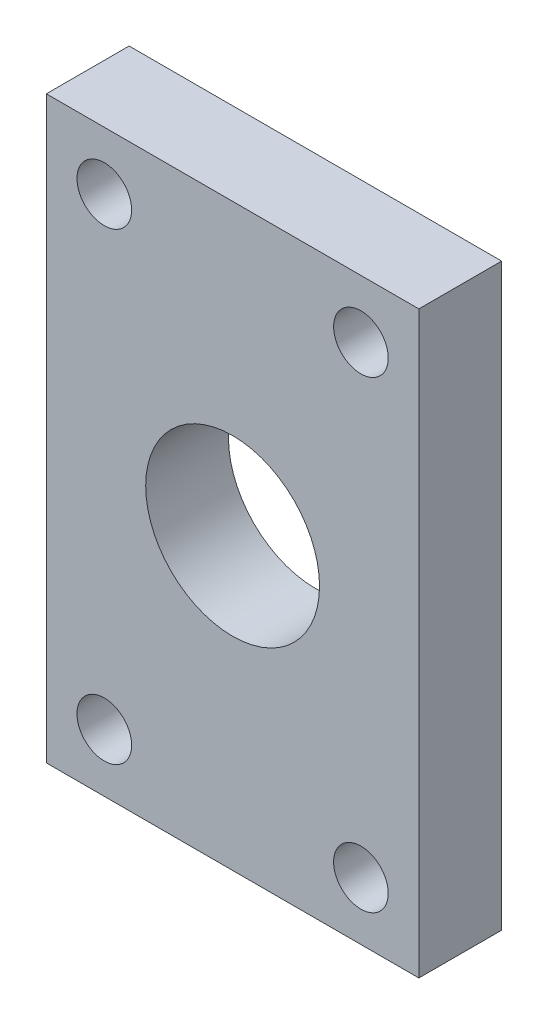
SolidWorks part; units mm, degrees
ref_plane "Piano frontale" through (0, 0, 0) normal (0, 0, 1) x (1, 0, 0)
ref_plane "Piano superiore" through (0, 0, 0) normal (0, 1, 0) x (1, 0, 0)
ref_plane "Piano destro" through (0, 0, 0) normal (1, 0, 0) x (0, 0, -1)
sketch "Schizzo1" plane through (0, 0, 0) normal (0, 0, 1) x (1, 0, 0)
  line L1 (0, 0) -> (45, 0)
  line L2 (0, 0) -> (0, 70)
  line L3 (0, 70) -> (45, 70)
  line L4 (45, 0) -> (45, 70)
  dimension "D1" = 70
  dimension "D2" = 45
extrude "Estrusione-Estrusione1" add sketch "Schizzo1" against normal blind 10
sketch "Schizzo2" plane through (0, 0, 0) normal (0, 0, 1) x (1, 0, 0)
  line L0 (22.5, 70) -> (22.5, 0) construction
  line L1 (45, 70) -> (0, 70) construction
  line L2 (0, 0) -> (45, 0) construction
  line L3 (45, 0) -> (23.1103, 0) construction
  line L4 (45, 0) -> (45, 70) construction
  line L5 (45, 35) -> (22.5, 35) construction
  line L6 (45, 7) -> (23.1103, 7) construction
  line L7 (45, 0) -> (45, 31.4323) construction
  line L8 (38, 0) -> (38, 31.4323) construction
  circle A0 centre (22.5, 35) radius 10.5
  circle A1 centre (38, 7) radius 3.3
  circle A2 centre (38, 63) radius 3.3
  circle A3 centre (7, 7) radius 3.3
  circle A4 centre (7, 63) radius 3.3
  dimension "D1" = 21
  dimension "D4" = 6.6
  dimension "D2" = 7
  dimension "D3" = 7
extrude "Taglio-Estrusione1" cut sketch "Schizzo2" against normal blind 10
